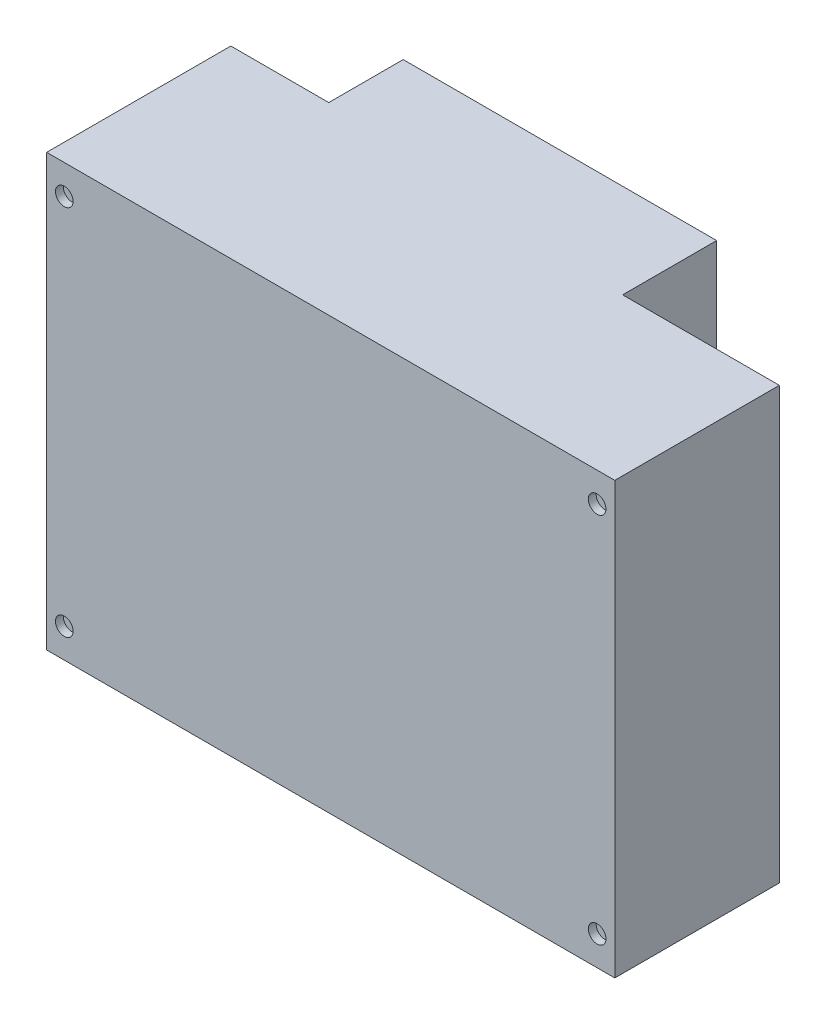
SolidWorks part; units mm, degrees
ref_plane "Front Plane" through (0, 0, 0) normal (0, 0, 1) x (1, 0, 0)
ref_plane "Top Plane" through (0, 0, 0) normal (0, 1, 0) x (1, 0, 0)
ref_plane "Right Plane" through (0, 0, 0) normal (1, 0, 0) x (0, 0, -1)
sketch "Sketch1" plane through (0, 0, 0) normal (0, 0, 1) x (1, 0, 0)
  line L0 (0, 0) -> (-72.5, 0) construction
  line L1 (-72.5, -55) -> (72.5, -55)
  line L2 (-72.5, -55) -> (-72.5, 55)
  line L3 (-72.5, 55) -> (72.5, 55)
  line L4 (72.5, -55) -> (72.5, 55)
  line L5 (-72.5, -55) -> (72.5, 55) construction
  line L6 (-72.5, 55) -> (72.5, -55) construction
  line L7 (0, 0) -> (0, 55) construction
  circle A0 centre (-68, -47.5) radius 2.25
  circle A1 centre (68, -47.5) radius 2.25
  circle A2 centre (68, 47.5) radius 2.25
  circle A3 centre (-68, 47.5) radius 2.25
  point P0 (0, 0)
  dimension "D3" = 4.5
  dimension "D1" = 145
  dimension "D2" = 110
  dimension "D4" = 4.5
  dimension "D5" = 7.5
  dimension "D6" = 136
  dimension "D7" = 95
  dimension "D8" = 136
extrude "Boss-Extrude1" add sketch "Sketch1" along normal blind 2
sketch "Sketch3" plane through (0, 0, 0) normal (0, 1, 0) x (1, 0, 0)
  line L0 (-72.5, 0) -> (-72.5, 45)
  line L1 (-72.5, 45) -> (-47.5, 45)
  line L2 (-47.5, 45) -> (-47.5, 64)
  line L3 (-47.5, 64) -> (32.5, 64)
  line L4 (32.5, 64) -> (32.5, 40)
  line L5 (32.5, 40) -> (72.5, 40)
  line L6 (72.5, 40) -> (72.5, 0)
  line L7 (72.5, 0) -> (-72.5, 0)
  dimension "D1" = 25
  dimension "D2" = 80
  dimension "D3" = 40
  dimension "D4" = 45
  dimension "D5" = 64
  dimension "D6" = 40
extrude "Boss-Extrude2" add sketch "Sketch3" along normal through all and the other way through all
